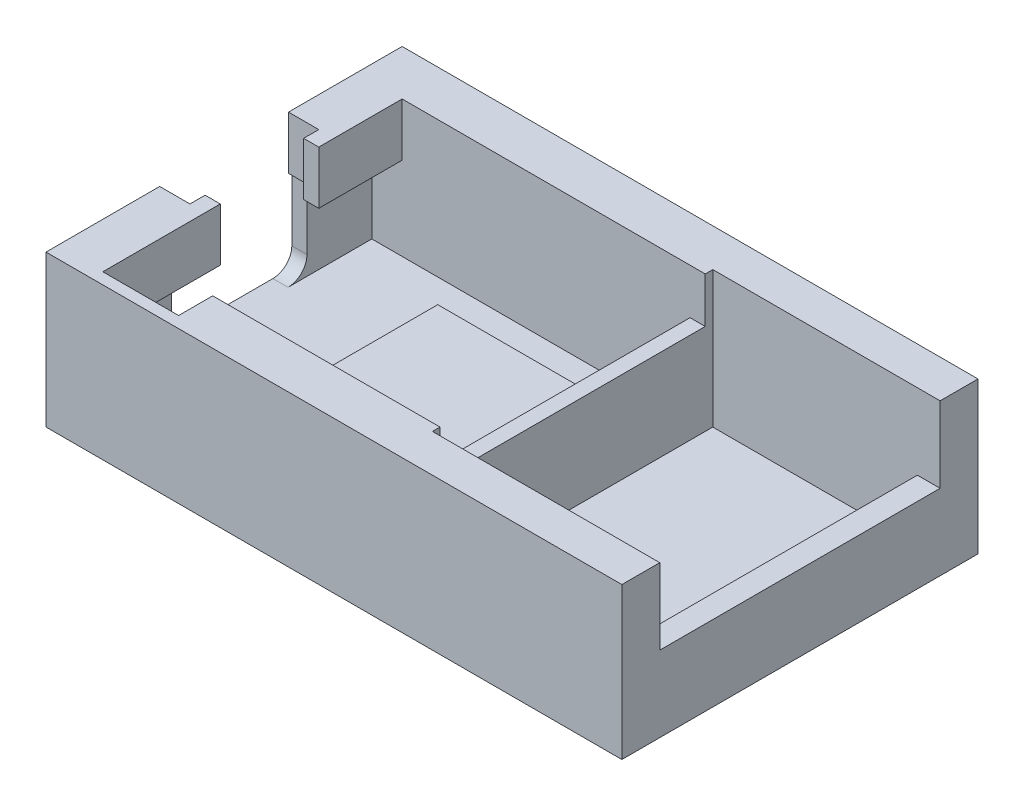
SolidWorks part; units mm, degrees
ref_plane "Front Plane" through (0, 0, 0) normal (0, 0, 1) x (1, 0, 0)
ref_plane "Top Plane" through (0, 0, 0) normal (0, 1, 0) x (1, 0, 0)
ref_plane "Right Plane" through (0, 0, 0) normal (1, 0, 0) x (0, 0, -1)
sketch "Sketch1" plane through (0, 0, 0) normal (0, 1, 0) x (1, 0, 0)
  line L1 (0, 0) -> (40, 0)
  line L2 (0, 0) -> (0, 24)
  line L3 (0, 24) -> (40, 24)
  line L4 (40, 0) -> (40, 24)
  dimension "D1" = 24
  dimension "D2" = 40
extrude "Boss-Extrude1" add sketch "Sketch1" along normal blind 1
sketch "Sketch2" plane through (0, 1, 0) normal (0, 1, 0) x (1, 0, 0)
  line L1 (0, 24) -> (40, 24)
  line L2 (0, 24) -> (0, 0)
  line L3 (0, 0) -> (40, 0)
  line L4 (40, 24) -> (40, 0)
  line L5 (1, 20.75) -> (22, 20.75)
  line L6 (1, 20.75) -> (1, 3.25)
  line L7 (1, 3.25) -> (22, 3.25)
  line L8 (22, 20.75) -> (22, 3.25)
  line L9 (23, 21.25) -> (36, 21.25)
  line L10 (23, 21.25) -> (23, 2.75)
  line L11 (23, 2.75) -> (36, 2.75)
  line L12 (36, 21.25) -> (36, 2.75)
  dimension "D1" = 17.5
  dimension "D2" = 21
  dimension "D3" = 3.25
  dimension "D4" = 1
  dimension "D5" = 18.5
  dimension "D6" = 13
  dimension "D7" = 1
  dimension "D8" = 2.75
extrude "Boss-Extrude3" add sketch "Sketch2" along normal blind 9
sketch "Sketch3" plane through (0, 10, 0) normal (0, 1, 0) x (1, 0, 0)
  line L0 (22, 20.75) -> (23, 20.75)
  line L1 (23, 21.25) -> (23, 2.75) construction
  line L2 (22, 20.75) -> (22, 3.25)
  line L3 (22, 3.25) -> (23, 3.25)
  line L4 (23, 21.25) -> (23, 2.75) construction
  line L5 (23, 3.25) -> (23, 20.75)
extrude "Cut-Extrude2" cut sketch "Sketch3" against normal blind 3
sketch "Sketch4" plane through (0, 1, 0) normal (0, 1, 0) x (1, 0, 0)
  line L0 (22, 20.75) -> (22, 3.25) construction
  line L1 (8.14, 17.96) -> (18.38, 17.96)
  line L2 (8.14, 17.96) -> (8.14, 6.04)
  line L3 (8.14, 6.04) -> (18.38, 6.04)
  line L4 (18.38, 17.96) -> (18.38, 6.04)
  line L5 (22, 20.75) -> (1, 20.75) construction
  line L6 (1, 3.25) -> (22, 3.25) construction
  line L7 (1, 20.75) -> (1, 3.25) construction
  dimension "D1" = 3.62
  dimension "D2" = 2.79
  dimension "D3" = 2.79
  dimension "D4" = 7.14
extrude "Boss-Extrude4" add sketch "Sketch4" along normal blind 1.21
sketch "Sketch5" plane through (1, 0, 0) normal (1, 0, 0) x (0, 0, -1)
  line L0 (7.53, 2.25) -> (7.53, 2.96)
  line L1 (8.78, 1) -> (15.22, 1)
  line L3 (16.47, 2.96) -> (16.47, 2.25)
  line L4 (20.75, 1) -> (3.25, 1) construction
  line L5 (3.25, 10) -> (3.25, 1) construction
  line L6 (7.53, 2.96) -> (7.53, 10)
  line L7 (20.75, 10) -> (3.25, 10) construction
  line L8 (7.53, 10) -> (16.47, 10)
  line L9 (16.47, 10) -> (16.47, 2.96)
  line L10 (20.75, 10) -> (20.75, 1) construction
  arc A0 (7.53, 2.25) -> (8.78, 1) centre (8.78, 2.25) ccw
  arc A3 (15.22, 1) -> (16.47, 2.25) centre (15.22, 2.25) ccw
  dimension "D7" = 1.25
  dimension "D1" = 1.25
  dimension "D2" = 0.71
  dimension "D3" = 6.44
  dimension "D4" = 4.28
  dimension "D9" = 0.71
  dimension "D10" = 4.28
extrude "Cut-Extrude3" cut sketch "Sketch5" against normal blind 2
sketch "Sketch8" plane through (0, 10, 0) normal (0, 1, 0) x (1, 0, 0)
  line L0 (36, 21.25) -> (40, 21.25)
  line L1 (40, 0) -> (40, 24) construction
  line L2 (36, 2.75) -> (40, 2.75)
  line L3 (40, 2.75) -> (40, 21.25)
  line L4 (36, 21.25) -> (36, 2.75)
extrude "Cut-Extrude4" cut sketch "Sketch8" against normal blind 5
sketch "Sketch10" plane through (0, 10, 0) normal (0, 1, 0) x (1, 0, 0)
sketch "Sketch11" plane through (40, 0, 0) normal (1, 0, 0) x (0, 0, -1)
  line L0 (21.25, 10) -> (24, 10) construction
  line L1 (0, 0) -> (24, 0)
  line L2 (0, 0) -> (0, 10)
  line L3 (0, 10) -> (24, 10)
  line L4 (24, 0) -> (24, 10)
  line L5 (24, 10) -> (24, 0) construction
extrude "Cut-Extrude5" cut sketch "Sketch11" against normal blind 2
sketch "Sketch12" plane through (0, 10, 0) normal (0, 1, 0) x (1, 0, 0)
  line L0 (0, 24) -> (0, 16.47) construction
  line L1 (4, 1) -> (8, 1)
  line L2 (4, 1) -> (4, 4)
  line L3 (4, 4) -> (8, 4)
  line L4 (8, 1) -> (8, 4)
  line L5 (0, 0) -> (38, 0) construction
  dimension "D1" = 4
  dimension "D2" = 1
  dimension "D3" = 3
  dimension "D4" = 4
extrude "Cut-Extrude6" cut sketch "Sketch12" against normal blind 3
sketch "Sketch13" plane through (0, 10, 0) normal (0, 1, 0) x (1, 0, 0)
  line L0 (23, 20.75) -> (1, 20.75) construction
  line L2 (1, 16.47) -> (1, 20.75)
  line L3 (1, 20.75) -> (3, 20.75)
  line L5 (3, 20.75) -> (3, 15.25)
  line L8 (1, 3.25) -> (3, 3.25)
  line L10 (1, 3.25) -> (4, 3.25) construction
  line L14 (2, 7.75) -> (0, 7.75)
  line L16 (0, 16.47) -> (1, 16.47)
  line L17 (0, 16.47) -> (0, 16.25)
  line L18 (0, 16.25) -> (2, 16.25)
  line L21 (0, 7.75) -> (0, 7.53)
  line L22 (1, 7.53) -> (1, 3.25)
  line L23 (0, 7.53) -> (1, 7.53)
  line L26 (3, 15.25) -> (2, 15.25)
  line L27 (2, 16.25) -> (2, 15.25)
  line L30 (3, 8.75) -> (2, 8.75)
  line L31 (2, 7.75) -> (2, 8.75)
  line L32 (3, 8.75) -> (3, 3.25)
  dimension "D1" = 0.22
  dimension "D2" = 0.22
  dimension "D3" = 2
  dimension "D4" = 2
  dimension "D5" = 1
  dimension "D6" = 1
  dimension "D7" = 1
  dimension "D8" = 1
extrude "Boss-Extrude5" add sketch "Sketch13" against normal blind 3.5
sketch "Sketch14" plane through (0, 10, 0) normal (0, 1, 0) x (1, 0, 0)
  line L1 (4, 1) -> (3, 1)
  line L2 (4, 1) -> (4, 3.25)
  line L3 (4, 3.25) -> (3, 3.25)
  line L4 (3, 1) -> (3, 3.25)
extrude "Cut-Extrude7" cut sketch "Sketch14" against normal blind 3
sketch "Sketch15" plane through (0, 0, -24) normal (0, 0, -1) x (-1, 0, 0)
  line L1 (-38, 0) -> (0, 0)
  line L2 (-38, 0) -> (-38, 10)
  line L3 (-38, 10) -> (0, 10)
  line L4 (0, 0) -> (0, 10)
extrude "Cut-Extrude8" cut sketch "Sketch15" against normal blind 0.25
sketch "Sketch16" plane through (0, 0, 0) normal (0, 0, 1) x (1, 0, 0)
  line L1 (0, 0) -> (38, 0)
  line L2 (0, 0) -> (0, 10)
  line L3 (0, 10) -> (38, 10)
  line L4 (38, 0) -> (38, 10)
extrude "Cut-Extrude9" cut sketch "Sketch16" against normal blind 0.25
sketch "Sketch17" plane through (36, 0, 0) normal (-1, 0, 0) x (0, 0, 1)
  line L1 (-21.25, 1) -> (-2.75, 1)
  line L2 (-21.25, 1) -> (-21.25, 5)
  line L3 (-21.25, 5) -> (-2.75, 5)
  line L4 (-2.75, 1) -> (-2.75, 5)
extrude "Cut-Extrude10" cut sketch "Sketch17" against normal blind 0.5
